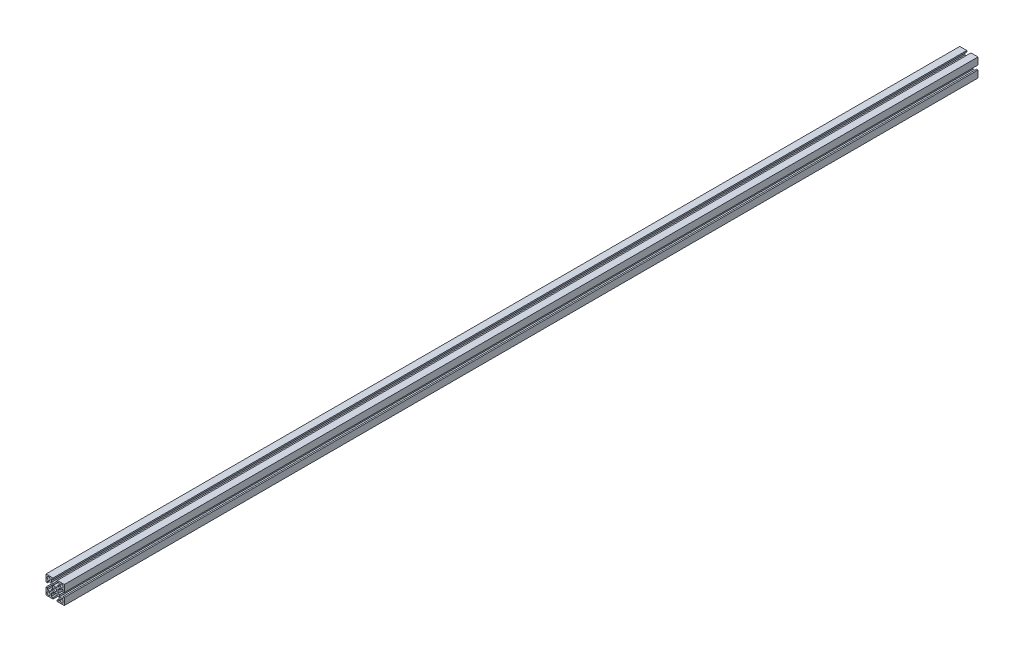
SolidWorks part; units mm, degrees
ref_plane "前视基准面" through (0, 0, 0) normal (0, 0, 1) x (1, 0, 0)
ref_plane "上视基准面" through (0, 0, 0) normal (0, 1, 0) x (1, 0, 0)
ref_plane "右视基准面" through (0, 0, 0) normal (1, 0, 0) x (0, 0, -1)
sketch "草图1" plane through (0, 0, 0) normal (0, 0, 1) x (1, 0, 0)
  line L0 (-2.1772, 9.243) -> (-9.8772, 9.243)
  line L1 (-9.8772, 9.243) -> (-9.8772, 1.543)
  line L2 (-2.1772, 7.743) -> (-4.1272, 7.743)
  line L3 (-2.1772, 4.043) -> (-4.1272, 4.043)
  line L4 (-2.1772, -3.657) -> (2.4228, -3.657)
  line L5 (-2.1772, 2.143) -> (2.4228, 2.143)
  line L6 (3.0228, 1.543) -> (3.0228, -3.057)
  line L7 (-2.7772, 1.543) -> (-2.7772, -3.057)
  line L8 (-4.1272, 7.743) -> (-4.1272, 4.043)
  line L9 (-2.1772, 9.243) -> (-2.1772, 7.743)
  line L10 (-2.1772, 4.043) -> (-2.1772, 2.143)
  line L11 (-8.3772, 1.543) -> (-8.3772, 3.493)
  line L12 (-4.6772, 1.543) -> (-4.6772, 3.493)
  line L13 (-8.3772, 3.493) -> (-4.6772, 3.493)
  line L14 (-9.8772, 1.543) -> (-8.3772, 1.543)
  line L15 (-4.6772, 1.543) -> (-2.7772, 1.543)
  line L16 (2.4228, 9.243) -> (10.1228, 9.243)
  line L17 (10.1228, 9.243) -> (10.1228, 1.543)
  line L18 (2.4228, 7.743) -> (4.3728, 7.743)
  line L19 (2.4228, 4.043) -> (4.3728, 4.043)
  line L20 (4.3728, 7.743) -> (4.3728, 4.043)
  line L21 (2.4228, 9.243) -> (2.4228, 7.743)
  line L22 (2.4228, 4.043) -> (2.4228, 2.143)
  line L23 (8.6228, 1.543) -> (8.6228, 3.493)
  line L24 (4.9228, 1.543) -> (4.9228, 3.493)
  line L25 (8.6228, 3.493) -> (4.9228, 3.493)
  line L26 (10.1228, 1.543) -> (8.6228, 1.543)
  line L27 (4.9228, 1.543) -> (3.0228, 1.543)
  line L28 (-2.1772, -10.757) -> (-9.8772, -10.757)
  line L29 (-9.8772, -10.757) -> (-9.8772, -3.057)
  line L30 (-2.1772, -9.257) -> (-4.1272, -9.257)
  line L31 (-2.1772, -5.557) -> (-4.1272, -5.557)
  line L32 (-4.1272, -9.257) -> (-4.1272, -5.557)
  line L33 (-2.1772, -10.757) -> (-2.1772, -9.257)
  line L34 (-2.1772, -5.557) -> (-2.1772, -3.657)
  line L35 (-8.3772, -3.057) -> (-8.3772, -5.007)
  line L36 (-4.6772, -3.057) -> (-4.6772, -5.007)
  line L37 (-8.3772, -5.007) -> (-4.6772, -5.007)
  line L38 (-9.8772, -3.057) -> (-8.3772, -3.057)
  line L39 (-4.6772, -3.057) -> (-2.7772, -3.057)
  line L40 (2.4228, -10.757) -> (10.1228, -10.757)
  line L41 (10.1228, -10.757) -> (10.1228, -3.057)
  line L42 (2.4228, -9.257) -> (4.3728, -9.257)
  line L43 (2.4228, -5.557) -> (4.3728, -5.557)
  line L44 (4.3728, -9.257) -> (4.3728, -5.557)
  line L45 (2.4228, -10.757) -> (2.4228, -9.257)
  line L46 (2.4228, -5.557) -> (2.4228, -3.657)
  line L47 (8.6228, -3.057) -> (8.6228, -5.007)
  line L48 (4.9228, -3.057) -> (4.9228, -5.007)
  line L49 (8.6228, -5.007) -> (4.9228, -5.007)
  line L50 (10.1228, -3.057) -> (8.6228, -3.057)
  line L51 (4.9228, -3.057) -> (3.0228, -3.057)
  circle A0 centre (0.1228, -0.757) radius 1.65
  circle A1 centre (-7.0022, 6.368) radius 1.75
  circle A2 centre (7.2478, 6.368) radius 1.75
  circle A3 centre (-7.0022, -7.882) radius 1.75
  circle A4 centre (7.2478, -7.882) radius 1.75
extrude "凸台-拉伸1" add sketch "草图1" along normal blind 1000
